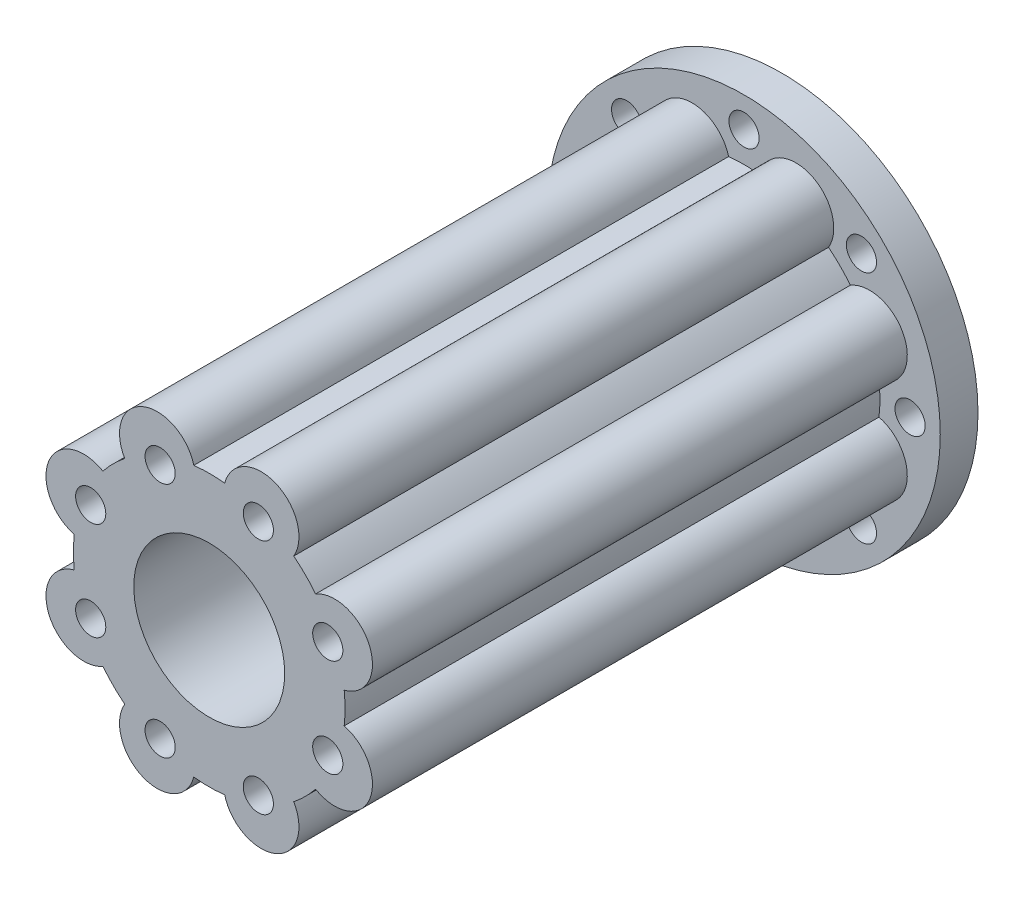
SolidWorks part; units mm, degrees
ref_plane "Alzado" through (0, 0, 0) normal (0, 0, 1) x (1, 0, 0)
ref_plane "Planta" through (0, 0, 0) normal (0, 1, 0) x (1, 0, 0)
ref_plane "Vista lateral" through (0, 0, 0) normal (1, 0, 0) x (0, 0, -1)
sketch "Croquis1" plane through (0, 0, 0) normal (0, 0, 1) x (1, 0, 0)
  circle A0 centre (0, 0) radius 13
  circle A1 centre (0, 0) radius 11 construction
  circle A2 centre (0, 11) radius 1
  circle A3 centre (7.7782, 7.7782) radius 1
  circle A4 centre (11, 0) radius 1
  circle A5 centre (7.7782, -7.7782) radius 1
  circle A6 centre (0, -11) radius 1
  circle A7 centre (-7.7782, -7.7782) radius 1
  circle A8 centre (-11, 0) radius 1
  circle A9 centre (-7.7782, 7.7782) radius 1
  dimension "D1" = 26
  dimension "D3" = 2
  dimension "D4" = 22
  dimension "D2" = 8
extrude "Saliente-Extruir1" add sketch "Croquis1" along normal blind 2.5
sketch "Croquis2" plane through (0, 0, 2.5) normal (0, 0, 1) x (1, 0, 0)
  circle A0 centre (0, 0) radius 5
  dimension "D1" = 10
extrude "Cortar-Extruir2" cut sketch "Croquis2" against normal blind 2.5
sketch "Croquis3" plane through (0, 0, 2.5) normal (0, 0, 1) x (1, 0, 0)
  circle A0 centre (0, 0) radius 5
  circle A1 centre (0, 0) radius 9
  dimension "D1" = 10
  dimension "D2" = 18
extrude "Saliente-Extruir2" add sketch "Croquis3" along normal up to surface (35.431 mm away)
sketch "Croquis4" plane through (0, 0, 37.931) normal (0, 0, 1) x (1, 0, 0)
  line L1 (8.3149, 3.4442) -> (3.4442, 8.3149) construction
  line L2 (3.4442, 8.3149) -> (-3.4442, 8.3149) construction
  line L3 (-3.4442, 8.3149) -> (-8.3149, 3.4442) construction
  line L4 (-8.3149, 3.4442) -> (-8.3149, -3.4442) construction
  line L5 (-8.3149, -3.4442) -> (-3.4442, -8.3149) construction
  line L6 (-3.4442, -8.3149) -> (3.4442, -8.3149) construction
  line L7 (3.4442, -8.3149) -> (8.3149, -3.4442) construction
  line L8 (8.3149, -3.4442) -> (8.3149, 3.4442) construction
  circle A1 centre (3.4442, 8.3149) radius 2.5
  circle A2 centre (8.3149, 3.4442) radius 2.5
  circle A3 centre (8.3149, -3.4442) radius 2.5
  circle A4 centre (3.4442, -8.3149) radius 2.5
  circle A5 centre (-3.4442, -8.3149) radius 2.5
  circle A6 centre (-8.3149, -3.4442) radius 2.5
  circle A7 centre (-8.3149, 3.4442) radius 2.5
  circle A8 centre (-3.4442, 8.3149) radius 2.5
  circle A9 centre (0, 0) radius 8.3149 construction
  circle A10 centre (0, 0) radius 9 construction
  dimension "D1" = 5
  dimension "D5" = 18
  dimension "D3" = 6.8883
  dimension "D4" = 8.3149
  dimension "D2" = 8
extrude "Saliente-Extruir3" add sketch "Croquis4" against normal up to next
sketch "Croquis5" plane through (0, 0, 37.931) normal (0, 0, 1) x (1, 0, 0)
  line L1 (7.853, 3.2528) -> (3.2528, 7.853) construction
  line L2 (3.2528, 7.853) -> (-3.2528, 7.853) construction
  line L3 (-3.2528, 7.853) -> (-7.853, 3.2528) construction
  line L4 (-7.853, 3.2528) -> (-7.853, -3.2528) construction
  line L5 (-7.853, -3.2528) -> (-3.2528, -7.853) construction
  line L6 (-3.2528, -7.853) -> (3.2528, -7.853) construction
  line L7 (3.2528, -7.853) -> (7.853, -3.2528) construction
  line L8 (7.853, -3.2528) -> (7.853, 3.2528) construction
  circle A0 centre (0, 0) radius 8.5 construction
  circle A1 centre (-3.2528, 7.853) radius 1
  circle A3 centre (3.2528, 7.853) radius 1
  circle A4 centre (7.853, 3.2528) radius 1
  circle A5 centre (7.853, -3.2528) radius 1
  circle A6 centre (3.2528, -7.853) radius 1
  circle A7 centre (-3.2528, -7.853) radius 1
  circle A8 centre (-7.853, -3.2528) radius 1
  circle A9 centre (-7.853, 3.2528) radius 1
  point P12 (0, 0)
  dimension "D1" = 2
  dimension "D2" = 8
  dimension "D3" = 17
extrude "Cortar-Extruir3" cut sketch "Croquis5" against normal blind 10
